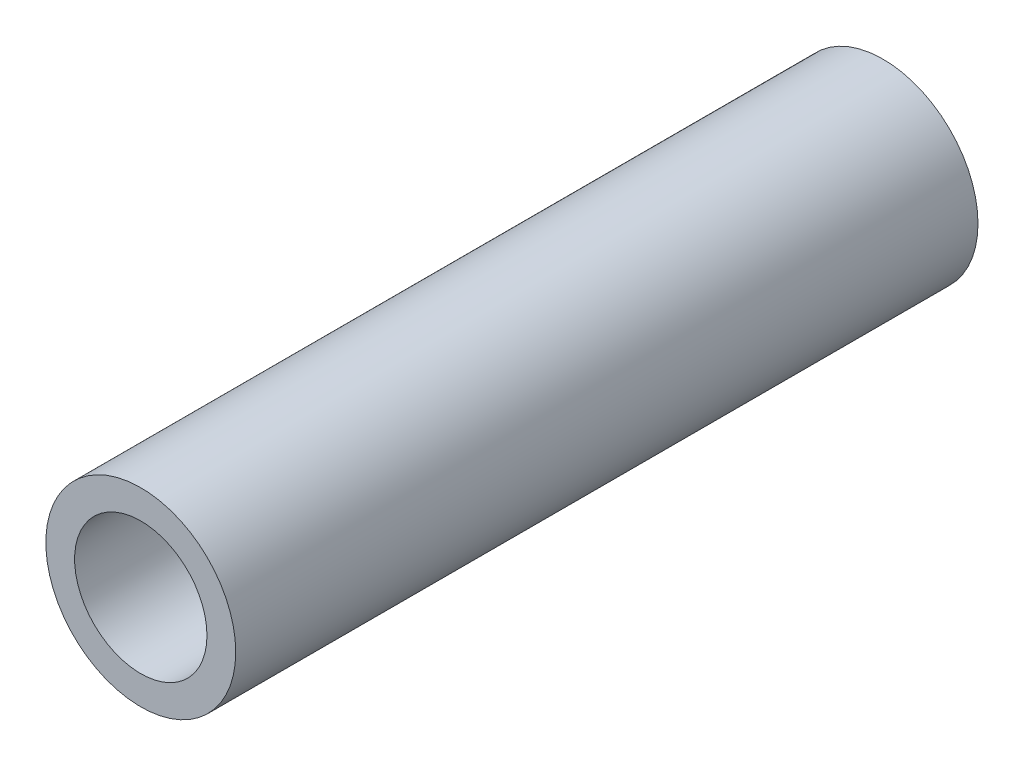
SolidWorks part; units mm, degrees
ref_plane "Front Plane" through (0, 0, 0) normal (0, 0, 1) x (1, 0, 0)
ref_plane "Top Plane" through (0, 0, 0) normal (0, 1, 0) x (1, 0, 0)
ref_plane "Right Plane" through (0, 0, 0) normal (1, 0, 0) x (0, 0, -1)
sketch "Sketch1" plane through (0, 0, 0) normal (0, 0, 1) x (1, 0, 0)
  circle A0 centre (0, 0) radius 2.921
  circle A1 centre (0, 0) radius 4.191
extrude "Boss-Extrude1" add sketch "Sketch1" along normal blind 32.766
